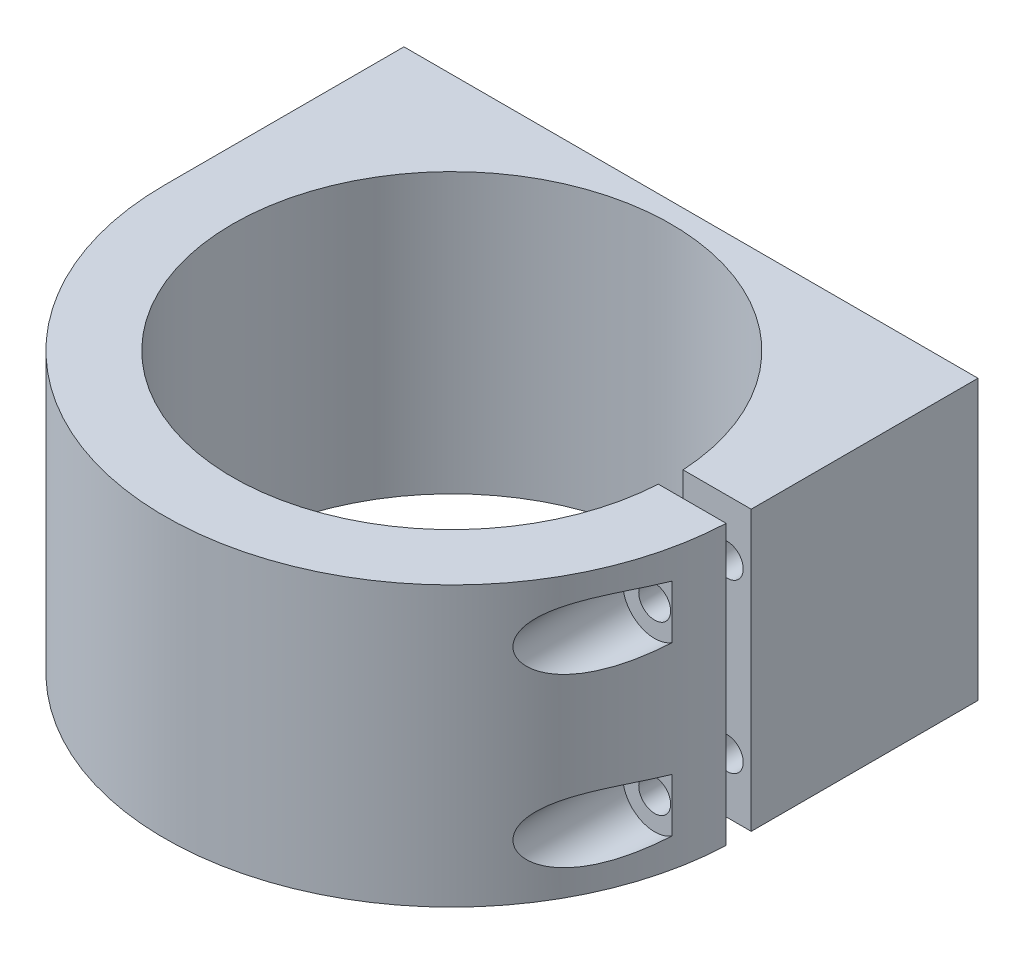
SolidWorks part; units mm, degrees
ref_plane "Front Plane" through (0, 0, 0) normal (0, 0, 1) x (1, 0, 0)
ref_plane "Top Plane" through (0, 0, 0) normal (0, 1, 0) x (1, 0, 0)
ref_plane "Right Plane" through (0, 0, 0) normal (1, 0, 0) x (0, 0, -1)
sketch "Sketch1" plane through (0, 0, 0) normal (0, 1, 0) x (1, 0, 0)
  line L0 (-36, 30) -> (-36, 0)
  line L1 (-36, 30) -> (36, 30)
  line L2 (27.4561, -1.553) -> (35.9665, -1.553)
  line L3 (36, 30) -> (36, 1.553)
  line L8 (36, 1.553) -> (27.4561, 1.553)
  arc A0 (27.4561, 1.553) -> (27.4561, -1.553) centre (0, 0) ccw
  arc A1 (-36, 0) -> (35.9665, -1.553) centre (0, 0) ccw
  dimension "D1" = 30
  dimension "D2" = 72
extrude "Boss-Extrude1" add sketch "Sketch1" along normal blind 35
sketch "Sketch2" plane through (0, 0, -30) normal (0, 0, -1) x (-1, 0, 0)
  line L1 (-33, 7) -> (33, 7) construction
  line L2 (-33, 7) -> (-33, 28) construction
  line L3 (-33, 28) -> (33, 28) construction
  line L4 (33, 7) -> (33, 28) construction
  line L5 (-33, 7) -> (33, 28) construction
  line L6 (-33, 28) -> (33, 7) construction
  circle A0 centre (-33, 28) radius 2
  circle A1 centre (33, 28) radius 2
  circle A2 centre (33, 7) radius 2
  circle A3 centre (-33, 7) radius 2
  point P0 (0, 17.5)
  dimension "D1" = 66
  dimension "D2" = 21
extrude "Cut-Extrude1" cut sketch "Sketch2" against normal through all
ref_plane "Plane1" through (0, 0, 7.553) normal (0, 0, -1) x (-1, 0, 0)
sketch "Sketch3" plane through (0, 0, 7.553) normal (0, 0, -1) x (-1, 0, 0)
  circle A0 centre (-33, 28) radius 4
  circle A1 centre (-33, 7) radius 4
  circle A2 centre (33, 28) radius 4
  circle A3 centre (33, 7) radius 4
extrude "Cut-Extrude2" cut sketch "Sketch3" against normal up to next
